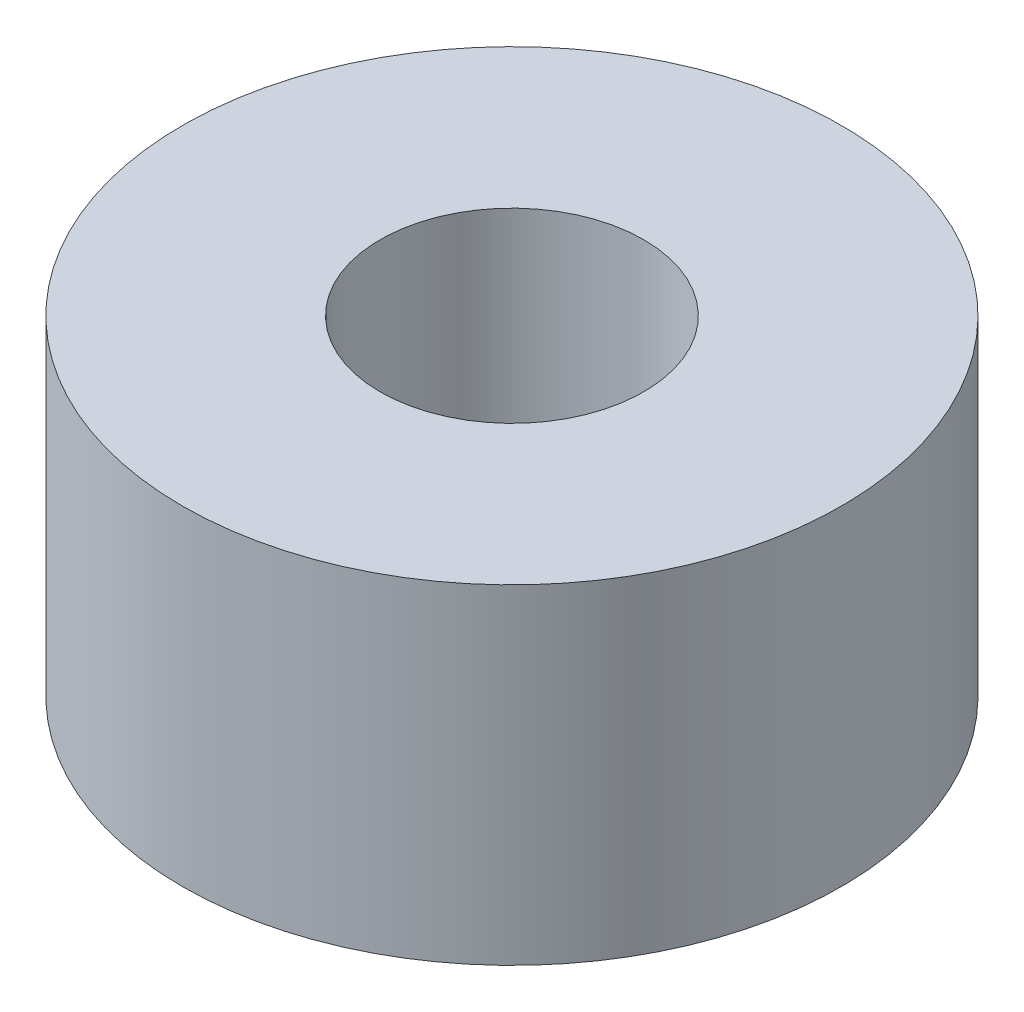
SolidWorks part; units mm, degrees
ref_plane "Front Plane" through (0, 0, 0) normal (0, 0, 1) x (1, 0, 0)
ref_plane "Top Plane" through (0, 0, 0) normal (0, 1, 0) x (1, 0, 0)
ref_plane "Right Plane" through (0, 0, 0) normal (1, 0, 0) x (0, 0, -1)
sketch "Sketch1" plane through (0, 0, 0) normal (0, 1, 0) x (1, 0, 0)
  circle A0 centre (0, 0) radius 2.5
  circle A1 centre (0, 0) radius 1
  dimension "D1" = 2
  dimension "D2" = 5
extrude "Boss-Extrude1" add sketch "Sketch1" along normal blind 2.5
